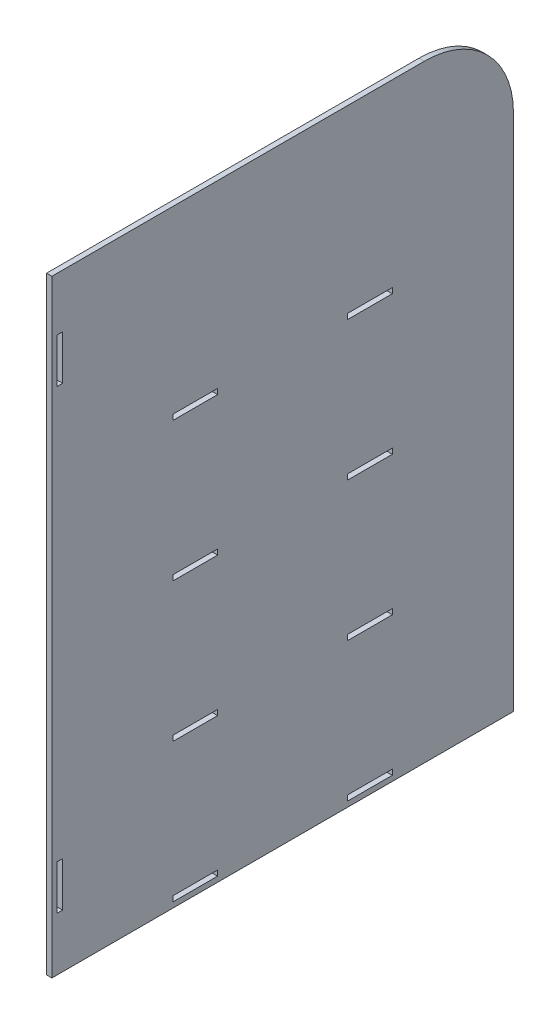
SolidWorks part; units mm, degrees
material "Maple"
ref_plane "Front Plane" through (0, 0, 0) normal (0, 0, 1) x (1, 0, 0)
ref_plane "Top Plane" through (0, 0, 0) normal (0, 1, 0) x (1, 0, 0)
ref_plane "Right Plane" through (0, 0, 0) normal (1, 0, 0) x (0, 0, -1)
sketch "Sketch1" plane through (0, 0, 0) normal (1, 0, 0) x (0, 0, -1)
  line L0 (-137.8318, -1.8488) -> (-396.8318, -1.8488) construction
  line L1 (-396.8318, 339.1512) -> (21.1682, 339.1512)
  line L2 (-396.8318, 339.1512) -> (-396.8318, -342.8488)
  line L3 (-396.8318, -342.8488) -> (121.1682, -342.8488)
  line L4 (121.1682, 239.1512) -> (121.1682, -342.8488)
  line L5 (-396.8318, 339.1512) -> (121.1682, -342.8488) construction
  line L6 (-396.8318, -342.8488) -> (121.1682, 339.1512) construction
  line L7 (-390.8318, 279.1512) -> (-384.8318, 279.1512)
  line L8 (-390.8318, 279.1512) -> (-390.8318, 229.1512)
  line L9 (-390.8318, 229.1512) -> (-384.8318, 229.1512)
  line L10 (-384.8318, 279.1512) -> (-384.8318, 229.1512)
  line L11 (-390.8318, -232.8488) -> (-384.8318, -232.8488)
  line L12 (-384.8318, -282.8488) -> (-384.8318, -232.8488)
  line L13 (-390.8318, -282.8488) -> (-384.8318, -282.8488)
  line L14 (-390.8318, -282.8488) -> (-390.8318, -232.8488)
  line L15 (-137.8318, -1.8488) -> (-137.8318, -342.8488) construction
  line L16 (-260.8318, -330.8488) -> (-210.8318, -330.8488)
  line L17 (-260.8318, -330.8488) -> (-260.8318, -336.8488)
  line L18 (-260.8318, -336.8488) -> (-210.8318, -336.8488)
  line L19 (-210.8318, -330.8488) -> (-210.8318, -336.8488)
  line L20 (-260.8318, -330.8488) -> (-210.8318, -336.8488) construction
  line L21 (-260.8318, -336.8488) -> (-210.8318, -330.8488) construction
  line L22 (-14.8318, -336.8488) -> (-64.8318, -336.8488)
  line L23 (-64.8318, -330.8488) -> (-64.8318, -336.8488)
  line L24 (-14.8318, -330.8488) -> (-64.8318, -330.8488)
  line L25 (-14.8318, -330.8488) -> (-14.8318, -336.8488)
  line L26 (-260.8318, -174.8488) -> (-260.8318, -180.8488)
  line L27 (-260.8318, -174.8488) -> (-210.8318, -174.8488)
  line L28 (-210.8318, -174.8488) -> (-210.8318, -180.8488)
  line L29 (-260.8318, -180.8488) -> (-210.8318, -180.8488)
  line L30 (-14.8318, -180.8488) -> (-64.8318, -180.8488)
  line L31 (-64.8318, -174.8488) -> (-64.8318, -180.8488)
  line L32 (-14.8318, -174.8488) -> (-64.8318, -174.8488)
  line L33 (-14.8318, -174.8488) -> (-14.8318, -180.8488)
  line L34 (-260.8318, -18.8488) -> (-260.8318, -24.8488)
  line L35 (-260.8318, -18.8488) -> (-210.8318, -18.8488)
  line L36 (-210.8318, -18.8488) -> (-210.8318, -24.8488)
  line L37 (-260.8318, -24.8488) -> (-210.8318, -24.8488)
  line L38 (-14.8318, -24.8488) -> (-64.8318, -24.8488)
  line L39 (-64.8318, -18.8488) -> (-64.8318, -24.8488)
  line L40 (-14.8318, -18.8488) -> (-64.8318, -18.8488)
  line L41 (-14.8318, -18.8488) -> (-14.8318, -24.8488)
  line L42 (-260.8318, 137.1512) -> (-260.8318, 131.1512)
  line L43 (-260.8318, 137.1512) -> (-210.8318, 137.1512)
  line L44 (-210.8318, 137.1512) -> (-210.8318, 131.1512)
  line L45 (-260.8318, 131.1512) -> (-210.8318, 131.1512)
  line L46 (-14.8318, 131.1512) -> (-64.8318, 131.1512)
  line L47 (-64.8318, 137.1512) -> (-64.8318, 131.1512)
  line L48 (-14.8318, 137.1512) -> (-64.8318, 137.1512)
  line L49 (-14.8318, 137.1512) -> (-14.8318, 131.1512)
  line L50 (-137.8318, -1.8488) -> (-137.8318, 339.1512) construction
  line L51 (-396.8318, 308.1512) -> (-137.8318, 308.1512) construction
  line L52 (-267.3318, 308.1512) -> (-267.3318, 344.969) construction
  line L64 (-140.8318, 333.1512) -> (-134.8318, 283.1512) construction
  line L65 (-140.8318, 283.1512) -> (-134.8318, 333.1512) construction
  arc A0 (121.1682, 239.1512) -> (21.1682, 339.1512) centre (21.1682, 239.1512) ccw
  point P0 (-137.8318, -1.8488)
  point P18 (-235.8318, -333.8488)
  dimension "D3" = 100
  dimension "D1" = 682
  dimension "D2" = 518
  dimension "D4" = 60
  dimension "D5" = 6
  dimension "D6" = 6
  dimension "D7" = 50
  dimension "D8" = 6
  dimension "D9" = 136
  dimension "D10" = 50
  dimension "D11" = 6
  dimension "D16" = 6
  dimension "D17" = 50
  dimension "D19" = 150
  dimension "D20" = 50
  dimension "D21" = 60
  dimension "D22" = 146
  dimension "D12" = 4
extrude "Boss-Extrude1" add sketch "Sketch1" along normal blind 6
